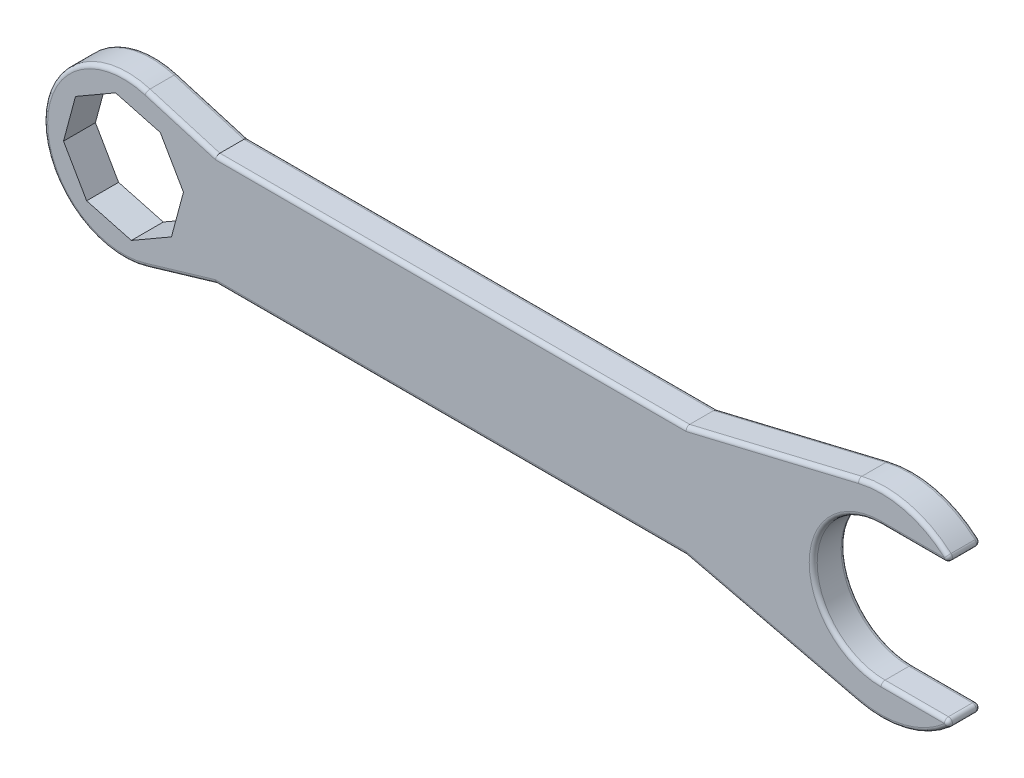
SolidWorks part; units mm, degrees
ref_plane "Front Plane" through (0, 0, 0) normal (0, 0, 1) x (1, 0, 0)
ref_plane "Top Plane" through (0, 0, 0) normal (0, 1, 0) x (1, 0, 0)
ref_plane "Right Plane" through (0, 0, 0) normal (1, 0, 0) x (0, 0, -1)
sketch "Sketch1" plane through (0, 0, 0) normal (0, 0, 1) x (1, 0, 0)
  line L0 (-457.9637, 0) -> (22440.2221, 0) construction
  line L1 (0, -457.9637) -> (0, 22440.2221) construction
  line L2 (29.1542, 8.5) -> (19.989, 8.5)
  line L3 (19.989, -8.5) -> (29.1542, -8.5)
  line L4 (-72.0789, 9.5902) -> (-63.3297, 7.0055)
  line L5 (-63.3297, 7.0055) -> (-4.4835, 7.0055)
  line L6 (-4.4835, 7.0055) -> (17.0846, 12.1579)
  line L7 (-72.0789, -9.5902) -> (-63.3297, -7.0055)
  line L8 (-4.4835, -7.0055) -> (17.0846, -12.1579)
  line L9 (-63.3297, -7.0055) -> (-4.4835, -7.0055)
  circle A0 centre (-74.9121, 0) radius 10
  arc A1 (29.1542, 8.5) -> (29.1542, -8.5) centre (19.989, 0) ccw
  arc A3 (19.989, 8.5) -> (19.989, -8.5) centre (19.989, 0) ccw
  dimension "D2" = 20
  dimension "D3" = 25
  dimension "D1" = 17
extrude "Boss-Extrude2" add sketch "Sketch1" along normal mid plane 4 contours A1 L6 L5 L4 A0 L7 L9 L8 | A3 L2 A1 L3 | A0
sketch "Sketch3" plane through (0, 0, 2) normal (0, 0, 1) x (1, 0, 0)
  line L1 (-75.8998, 7.5121) -> (-80.9223, 4.6135)
  line L2 (-80.9223, 4.6135) -> (-82.4242, -0.9877)
  line L3 (-82.4242, -0.9877) -> (-79.5255, -6.0103)
  line L4 (-79.5255, -6.0103) -> (-73.9244, -7.5121)
  line L5 (-73.9244, -7.5121) -> (-68.9018, -4.6135)
  line L6 (-68.9018, -4.6135) -> (-67.4, 0.9877)
  line L7 (-67.4, 0.9877) -> (-70.2986, 6.0103)
  line L8 (-70.2986, 6.0103) -> (-75.8998, 7.5121)
  circle A0 centre (-74.9121, 0) radius 7 construction
  point P1 (-78.4111, 6.0628)
  dimension "D1" = 14
extrude "Cut-Extrude1" cut sketch "Sketch3" against normal through all both and the other way through all
fillet "Fillet1" radius 0.5 2 edges at (29.1542, 8.5, 0) (29.1542, -8.5, 0)
fillet "Fillet2" radius 0.5 14 edges at (-67.7043, 8.2979, -2) (-84.9121, 0, -2) (6.3005, 9.5817, -2) (23.0103, 12.1294, -2) (28.394, 8.8232, -2) (23.9576, 8.5, -2) (11.489, 0, -2) (23.9576, -8.5, -2) (28.394, -8.8232, -2) (23.0103, -12.1294, -2) (-67.7043, -8.2979, -2) (6.3005, -9.5817, -2) (-33.9066, 7.0055, -2) (-33.9066, -7.0055, -2)
fillet "Fillet5" radius 0.5 1 edges at (-33.9066, 7.0055, 2)
fillet "Fillet6" radius 0.5 13 edges at (-66.858, 8.0479, 2) (-67.7043, -8.2979, 2) (6.3005, -9.5817, 2) (23.0103, -12.1294, 2) (28.394, -8.8232, 2) (23.9576, -8.5, 2) (11.489, 0, 2) (23.9576, 8.5, 2) (28.394, 8.8232, 2) (23.0103, 12.1294, 2) (-84.9121, 0, 2) (-33.9066, -7.0055, 2) (5.254, 9.3317, 2)
sketch "Sketch5" plane through (0, 0, -2) normal (0, 0, -1) x (-1, 0, 0)
  line L0 (15.7613, -0.8461) -> (35.7615, -0.8461) construction
  line L3 (15.7613, 3.8678) -> (35.7615, 3.8678)
  line L4 (15.7613, -5.5599) -> (35.7615, -5.5599)
  arc A2 (15.7613, 3.8678) -> (15.7613, -5.5599) centre (15.7613, -0.8461) ccw
  arc A3 (35.7615, -5.5599) -> (35.7615, 3.8678) centre (35.7615, -0.8461) ccw
  point P2 (25.7614, -0.8461)
extrude "Cut-Extrude4" cut sketch "Sketch5" along normal mid plane 3 from offset 0
sketch "Sketch6" plane through (0, 0, -0.5) normal (0, 0, -1) x (-1, 0, 0)
  text T0 "          17X15MM "
extrude "Boss-Extrude3" add sketch "Sketch6" along normal blind 1
